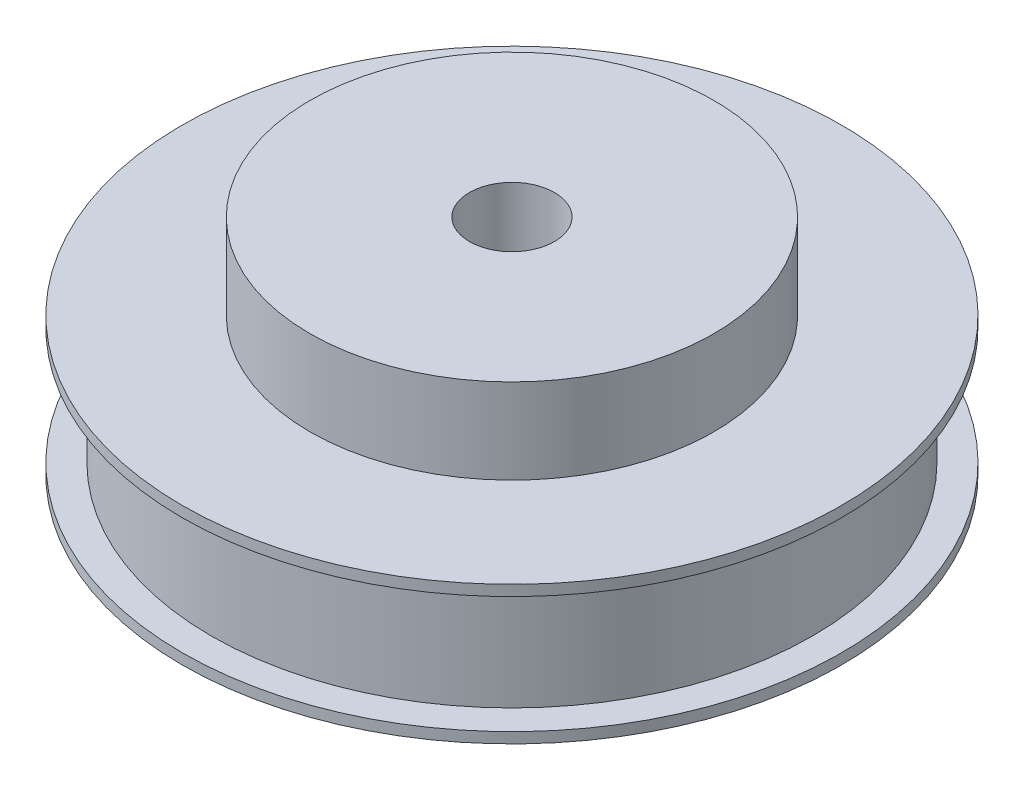
SolidWorks part; units mm, degrees
ref_plane "Спереди" through (0, 0, 0) normal (0, 0, 1) x (1, 0, 0)
ref_plane "Сверху" through (0, 0, 0) normal (0, 1, 0) x (1, 0, 0)
ref_plane "Справа" through (0, 0, 0) normal (1, 0, 0) x (0, 0, -1)
sketch "Эскиз1" plane through (0, 0, 0) normal (0, 1, 0) x (1, 0, 0)
  circle A0 centre (0, 0) radius 31
  dimension "D1" = 62
extrude "Бобышка-Вытянуть1" add sketch "Эскиз1" along normal blind 1
sketch "Эскиз2" plane through (0, 1, 0) normal (0, 1, 0) x (1, 0, 0)
  circle A0 centre (0, 0) radius 28.27
  dimension "D1" = 56.54
extrude "Бобышка-Вытянуть2" add sketch "Эскиз2" along normal blind 11
sketch "Эскиз3" plane through (0, 12, 0) normal (0, 1, 0) x (1, 0, 0)
  circle A0 centre (0, 0) radius 31
  dimension "D1" = 62
extrude "Бобышка-Вытянуть3" add sketch "Эскиз3" along normal blind 1
sketch "Эскиз4" plane through (0, 13, 0) normal (0, 1, 0) x (1, 0, 0)
  circle A0 centre (0, 0) radius 19
  dimension "D1" = 38
extrude "Бобышка-Вытянуть4" add sketch "Эскиз4" along normal blind 8
sketch "Эскиз5" plane through (0, 21, 0) normal (0, 1, 0) x (1, 0, 0)
  circle A0 centre (0, 0) radius 4
  dimension "D1" = 8
extrude "Вырез-Вытянуть1" cut sketch "Эскиз5" against normal through all contours A0
